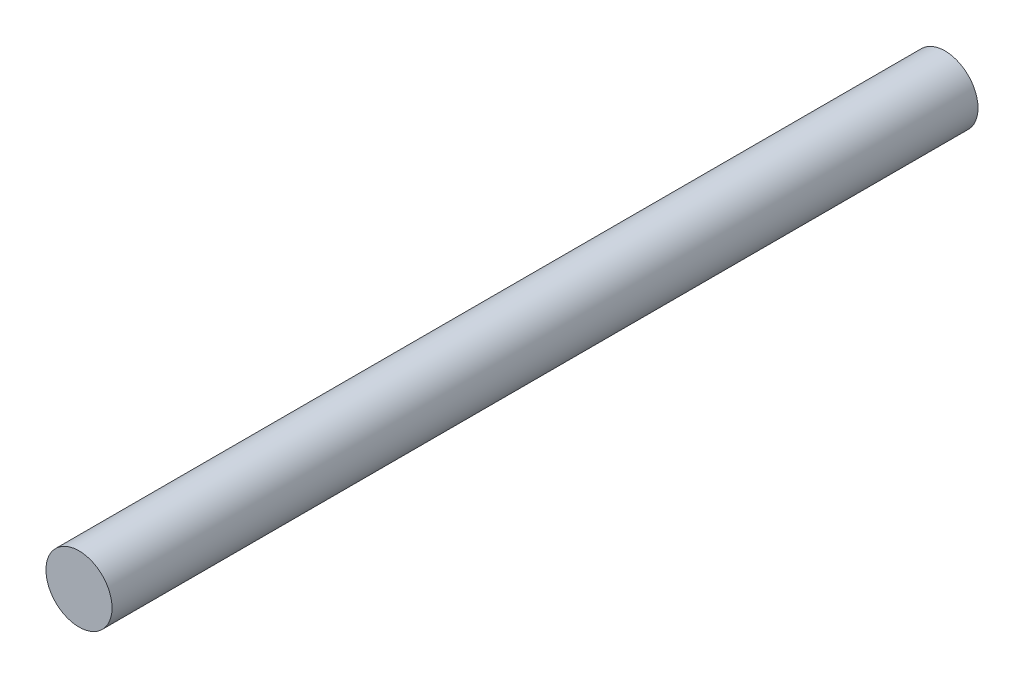
SolidWorks part; units mm, degrees
ref_plane "Přední rovina" through (0, 0, 0) normal (0, 0, 1) x (1, 0, 0)
ref_plane "Horní rovina" through (0, 0, 0) normal (0, 1, 0) x (1, 0, 0)
ref_plane "Pravá rovina" through (0, 0, 0) normal (1, 0, 0) x (0, 0, -1)
sketch "Skica1" plane through (0, 0, 0) normal (0, 0, 1) x (1, 0, 0)
  circle A0 centre (0, 0) radius 1
  dimension "D1" = 2
extrude "Přidat vysunutím1" add sketch "Skica1" along normal blind 26.2
